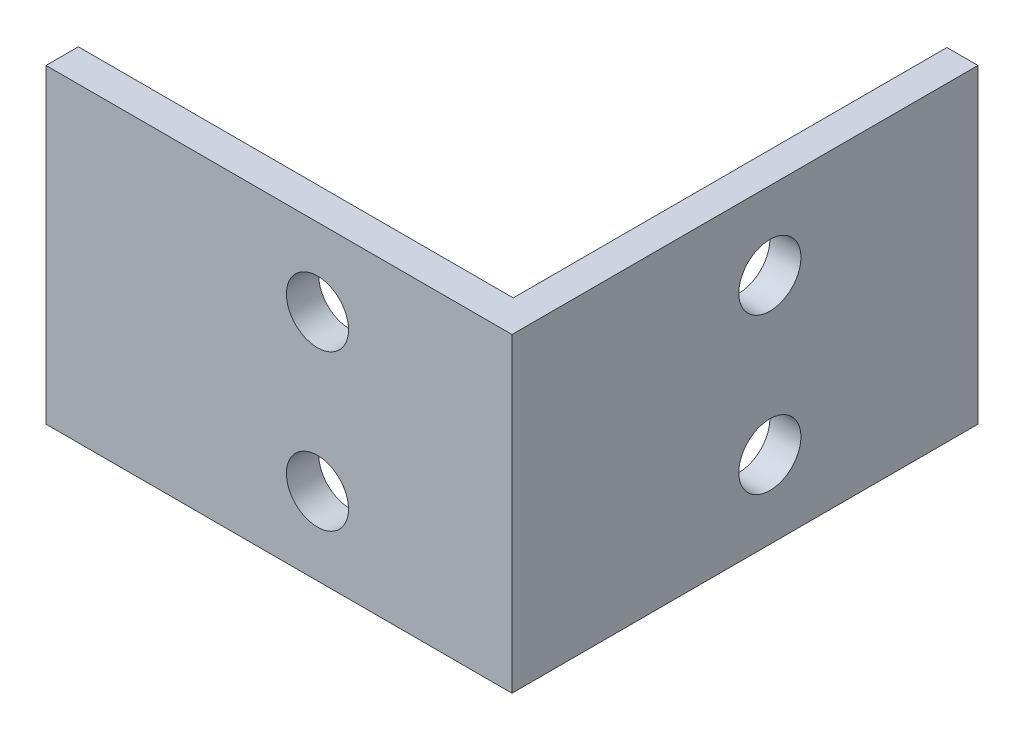
SolidWorks part; units mm, degrees
ref_plane "Front Plane" through (0, 0, 0) normal (0, 0, 1) x (1, 0, 0)
ref_plane "Top Plane" through (0, 0, 0) normal (0, 1, 0) x (1, 0, 0)
ref_plane "Right Plane" through (0, 0, 0) normal (1, 0, 0) x (0, 0, -1)
sketch "Sketch1" plane through (0, 0, 0) normal (0, 1, 0) x (1, 0, 0)
  line L0 (0, 13.4) -> (0, -14.52)
  line L1 (0, -14.52) -> (-28, -14.52)
  line L2 (-28, -14.52) -> (-28, -16.6)
  line L3 (-28, -16.6) -> (2, -16.6)
  line L4 (2, -16.6) -> (2, 13.4)
  line L5 (2, 13.4) -> (0, 13.4)
  dimension "D1" = 2
  dimension "D2" = 30
  dimension "D3" = 30
extrude "Boss-Extrude1" add sketch "Sketch1" along normal blind 20
sketch "Sketch2" plane through (2, 0, 0) normal (1, 0, 0) x (0, 0, -1)
  line L0 (-16.6, 20) -> (13.4, 20) construction
  circle A1 centre (0, 15) radius 2
  circle A2 centre (0, 5) radius 2
  dimension "D3" = 4
  dimension "D4" = 4
  dimension "D1" = 10
  dimension "D2" = 5
sketch "Sketch3" plane through (0, 0, 16.6) normal (0, 0, 1) x (1, 0, 0)
  line L0 (-28, 20) -> (2, 20) construction
  circle A1 centre (-10.5239, 15) radius 2
  circle A2 centre (-10.5239, 5) radius 2
  point P0 (0, 0)
  point P6 (-11.4458, 14.8631)
  dimension "D1" = 4
  dimension "D2" = 4
  dimension "D3" = 10
  dimension "D4" = 5
extrude "Cut-Extrude4" cut sketch "Sketch2" against normal up to next and the other way through all contours A1 | A2
extrude "Cut-Extrude5" cut sketch "Sketch3" against normal up to next contours A2 | A1
